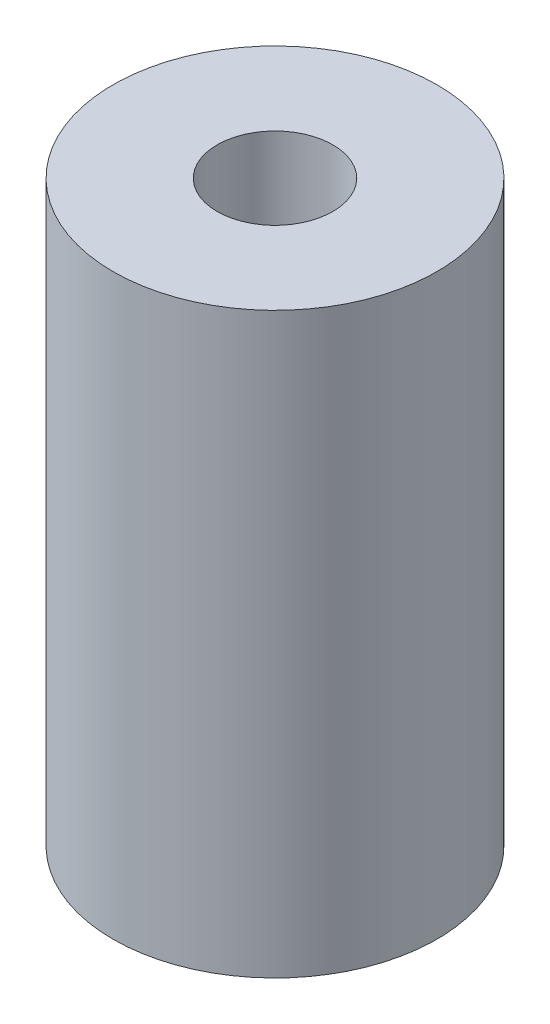
SolidWorks part; units mm, degrees
ref_plane "前视基准面" through (0, 0, 0) normal (0, 0, 1) x (1, 0, 0)
ref_plane "上视基准面" through (0, 0, 0) normal (0, 1, 0) x (1, 0, 0)
ref_plane "右视基准面" through (0, 0, 0) normal (1, 0, 0) x (0, 0, -1)
sketch "草图1" plane through (0, 0, 0) normal (0, 1, 0) x (1, 0, 0)
  circle A0 centre (0, 0) radius 7
  dimension "D1" = 14
extrude "凸台-拉伸1" add sketch "草图1" along normal blind 25
sketch "草图2" plane through (0, 25, 0) normal (0, 1, 0) x (1, 0, 0)
  circle A0 centre (0, 0) radius 2.5
  dimension "D1" = 5
extrude "切除-拉伸1" cut sketch "草图2" against normal blind 12
sketch "草图3" plane through (0, 0, 0) normal (0, -1, 0) x (1, 0, 0)
  circle A0 centre (0, 0) radius 4
  dimension "D1" = 8
extrude "切除-拉伸2" cut sketch "草图3" against normal blind 13
